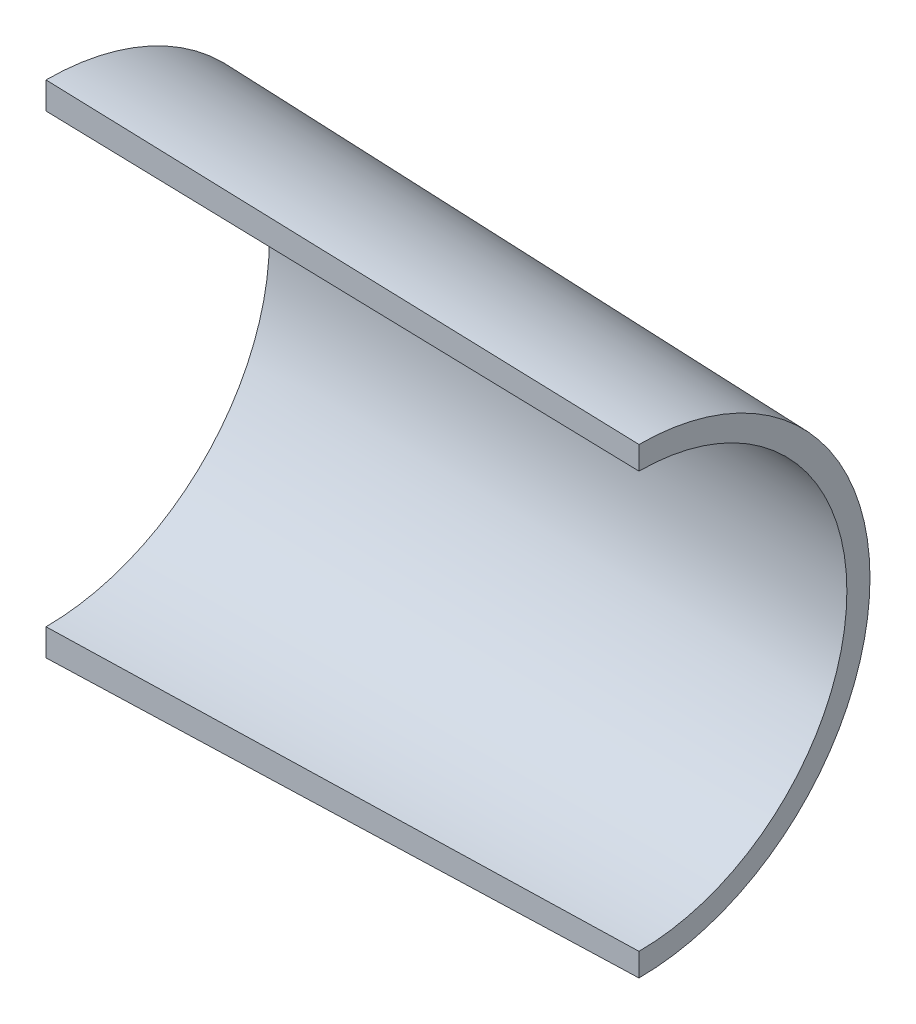
SolidWorks part; units mm, degrees
ref_plane "Front Plane" through (0, 0, 0) normal (0, 0, 1) x (1, 0, 0)
ref_plane "Top Plane" through (0, 0, 0) normal (0, 1, 0) x (1, 0, 0)
ref_plane "Right Plane" through (0, 0, 0) normal (1, 0, 0) x (0, 0, -1)
sketch "Sketch1" plane through (0, 0, 0) normal (0, 0, 1) x (1, 0, 0)
  line L0 (0, 0) -> (4000, 0) construction
  line L1 (1880, -580) -> (1880, -650)
  line L2 (1880, -650) -> (3420, -600)
  line L3 (3420, -600) -> (3420, -540)
  line L4 (3420, -540) -> (1880, -580)
revolve "Revolve1" add sketch "Sketch1" angle 180 about L0
